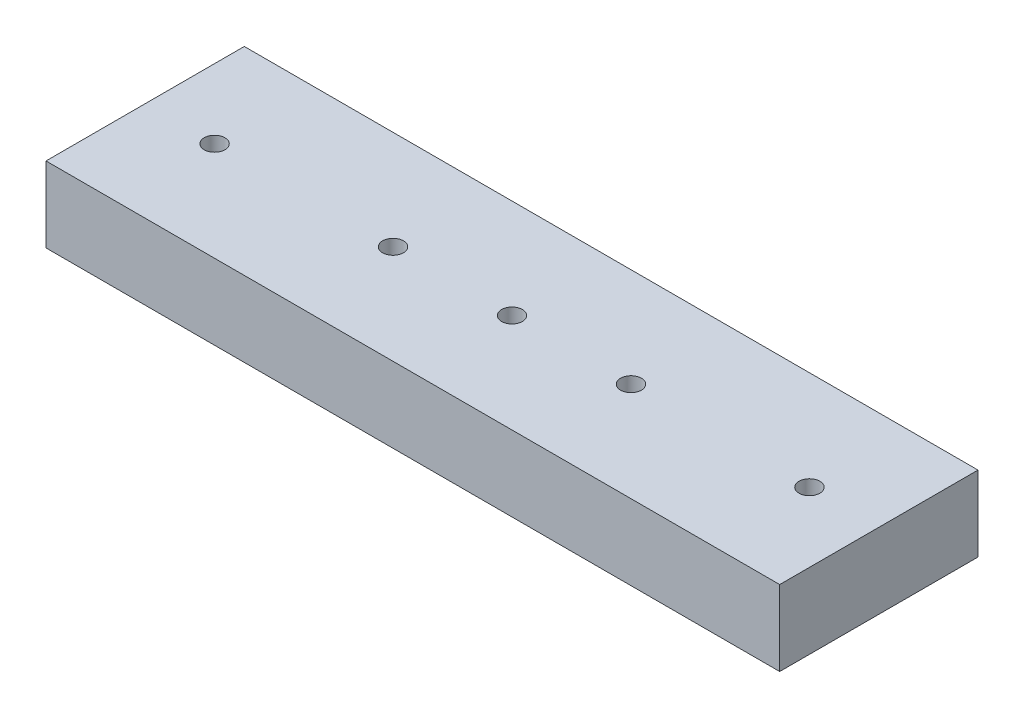
SolidWorks part; units mm, degrees
ref_plane "前视基准面" through (0, 0, 0) normal (0, 0, 1) x (1, 0, 0)
ref_plane "上视基准面" through (0, 0, 0) normal (0, 1, 0) x (1, 0, 0)
ref_plane "右视基准面" through (0, 0, 0) normal (1, 0, 0) x (0, 0, -1)
sketch "草图1" plane through (0, 0, 0) normal (0, 1, 0) x (1, 0, 0)
  line L1 (185, -50) -> (-185, -50)
  line L2 (185, -50) -> (185, 50)
  line L3 (185, 50) -> (-185, 50)
  line L4 (-185, -50) -> (-185, 50)
  line L5 (185, -50) -> (-185, 50) construction
  line L6 (185, 50) -> (-185, -50) construction
  point P0 (0, 0)
  dimension "D1" = 370
  dimension "D2" = 100
extrude "凸台-拉伸1" add sketch "草图1" along normal blind 38
hole_wizard "M12x1.25 螺纹孔1" positions "草图3" profile "草图4" tap size "M12x1.25" standard "GB" end condition through all
sketch "草图3" plane through (0, 38, 0) normal (0, 1, 0) x (1, 0, 0)
  line L0 (-185, 50) -> (-185, -50) construction
  line L1 (185, 50) -> (-185, 50) construction
  point P0 (-150, 0)
  dimension "D1" = 35
  dimension "D2" = 50
sketch "草图4" plane through (-150, 38, 0) normal (1, 0, 0) x (0, 0, 1)
  line L0 (0, 0) -> (0, 38)
  line L1 (0, 38) -> (5.25, 38)
  line L2 (5.25, 38) -> (5.25, 0)
  line L5 (5.25, 0) -> (0, 0)
  line L11 (0, -6.35) -> (0, 107.95) construction
  dimension "通孔螺纹孔钻头直径" = 10.5
  dimension "通孔螺纹孔钻头深度" = 38
cosmetic thread "孔螺蚊线1" parameters "D2"=12
pattern_linear "阵列(线性)1" count 2 spacing 90 along (1, 0, 0) of "M12x1.25 螺纹孔1"
pattern_linear "阵列(线性)3" count 2 spacing 150 along (1, 0, 0) of "M12x1.25 螺纹孔1"
pattern_linear "阵列(线性)4" count 2 spacing 210 along (1, 0, 0) of "M12x1.25 螺纹孔1"
pattern_linear "阵列(线性)5" count 2 spacing 300 along (1, 0, 0) of "M12x1.25 螺纹孔1"
